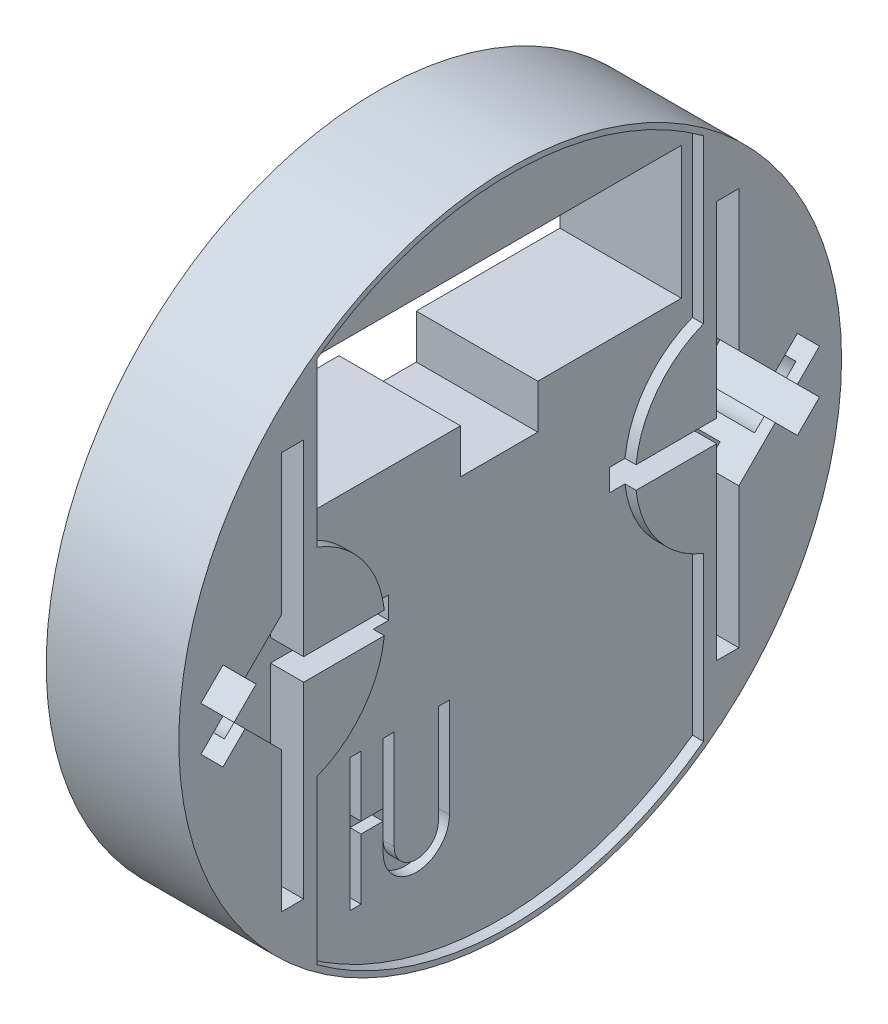
SolidWorks part; units mm, degrees
ref_plane "Front Plane" through (0, 0, 0) normal (0, 0, 1) x (1, 0, 0)
ref_plane "Top Plane" through (0, 0, 0) normal (0, 1, 0) x (1, 0, 0)
ref_plane "Right Plane" through (0, 0, 0) normal (1, 0, 0) x (0, 0, -1)
sketch "Sketch1" plane through (0, 0, 0) normal (1, 0, 0) x (0, 0, -1)
  line L2 (0, -17.4878) -> (0, 20.0189) construction
  circle A0 centre (0, 0) radius 15
  dimension "D1" = 30
extrude "Boss-Extrude1" add sketch "Sketch1" along normal blind 6
sketch "Sketch2" plane through (6, 0, 0) normal (1, 0, 0) x (0, 0, -1)
  line L0 (-8.75, 11.8743) -> (-8.75, 4.5)
  line L1 (0, -13.6401) -> (0, 12.421) construction
  line L2 (-8.75, -4.5) -> (-8.75, -11.8743)
  line L3 (8.75, -4.5) -> (8.75, -11.8743)
  line L4 (8.75, 11.8743) -> (8.75, 4.5)
  arc A0 (-8.75, -11.8743) -> (8.75, -11.8743) centre (0, 0) ccw
  arc A1 (-8.75, -4.5) -> (-8.75, 4.5) centre (-10.5, 0) ccw
  arc A2 (8.75, -4.5) -> (8.75, 4.5) centre (10.5, 0) cw
  arc A3 (8.75, 11.8743) -> (-8.75, 11.8743) centre (0, 0) ccw
  dimension "D1" = 29.5
  dimension "D3" = 8.75
  dimension "D4" = 10.5
  dimension "D2" = 8.75
  dimension "D5" = 9
extrude "Cut-Extrude1" cut sketch "Sketch2" against normal blind 0.5
sketch "Sketch3" plane through (5.5, 0, 0) normal (1, 0, 0) x (0, 0, -1)
  line L4 (-8.25, 11.5) -> (-8.25, 5.5)
  line L5 (-8.25, 5.5) -> (-1.75, 5.5)
  line L6 (-1.75, 5.5) -> (-1.75, 3.5)
  line L7 (-1.75, 3.5) -> (1.75, 3.5)
  line L8 (1.75, 3.5) -> (1.75, 5.5)
  line L9 (1.75, 5.5) -> (8.25, 5.5)
  line L10 (8.25, 5.5) -> (8.25, 11.5)
  line L11 (8.25, 11.5) -> (-8.25, 11.5)
  line L12 (-8.75, 11.8743) -> (-8.75, 4.5) construction
  line L13 (8.75, 4.5) -> (8.75, 11.8743) construction
  circle A5 centre (0, 0) radius 15 construction
  dimension "D1" = 11.5
  dimension "D2" = 0.5
  dimension "D3" = 0.5
  dimension "D4" = 8
  dimension "D5" = 2
  dimension "D6" = 3.5
extrude "Cut-Extrude2" cut sketch "Sketch3" against normal through all
sketch "Sketch4" plane through (6, 0, 0) normal (1, 0, 0) x (0, 0, -1)
  line L0 (-9.35, 9) -> (-9.35, 0.5)
  line L1 (-9.35, -9) -> (-10.35, -9)
  line L2 (-10.35, -9) -> (-10.35, -2.65)
  line L3 (-10.35, -2.65) -> (-12, -1)
  line L4 (-12, -1) -> (-13, -2)
  line L5 (-13, -2) -> (-14, -1)
  line L6 (-14, -1) -> (-13, 0)
  line L7 (-13, 0) -> (-14, 1)
  line L8 (-14, 1) -> (-13, 2)
  line L9 (-13, 2) -> (-12, 1)
  line L10 (-12, 1) -> (-10.35, 2.65)
  line L11 (-10.35, 2.65) -> (-10.35, 9)
  line L12 (-10.35, 9) -> (-9.35, 9)
  line L13 (0, 10.0376) -> (0, -10.6716) construction
  line L14 (-9.35, 0.5) -> (-5, 0.5)
  line L15 (-5, 0.5) -> (-5, -0.5)
  line L16 (-5, -0.5) -> (-9.35, -0.5)
  line L17 (-9.35, -0.5) -> (-9.35, -9)
  line L18 (-8.75, 11.8743) -> (-8.75, 4.5) construction
  line L19 (-5, 0) -> (0, 0) construction
  line L20 (9.35, -0.5) -> (9.35, -9)
  line L21 (5, -0.5) -> (9.35, -0.5)
  line L22 (5, 0.5) -> (5, -0.5)
  line L23 (9.35, 0.5) -> (5, 0.5)
  line L24 (10.35, 9) -> (9.35, 9)
  line L25 (10.35, 2.65) -> (10.35, 9)
  line L26 (12, 1) -> (10.35, 2.65)
  line L27 (13, 2) -> (12, 1)
  line L28 (14, 1) -> (13, 2)
  line L29 (13, 0) -> (14, 1)
  line L30 (14, -1) -> (13, 0)
  line L31 (13, -2) -> (14, -1)
  line L32 (12, -1) -> (13, -2)
  line L33 (10.35, -2.65) -> (12, -1)
  line L34 (10.35, -9) -> (10.35, -2.65)
  line L35 (9.35, -9) -> (10.35, -9)
  line L36 (9.35, 9) -> (9.35, 0.5)
  dimension "D1" = 1
  dimension "D2" = 1
  dimension "D3" = 0.6
  dimension "D4" = 18
  dimension "D5" = 9
  dimension "D6" = 5
  dimension "D7" = 1
  dimension "D8" = 1
  dimension "D9" = 8
  dimension "D10" = 1
extrude "Cut-Extrude4" cut sketch "Sketch4" against normal blind 1.5
sketch "Sketch5" plane through (4.5, 0, 0) normal (1, 0, 0) x (0, 0, -1)
  line L0 (-12, -1) -> (-13, -2)
  line L1 (-13, -2) -> (-14, -1)
  line L2 (-14, -1) -> (-13, 0)
  line L3 (-13, 0) -> (-14, 1)
  line L4 (-14, 1) -> (-13, 2)
  line L5 (-13, 2) -> (-12, 1)
  line L6 (-12, -3.4515) -> (-12, 3.0113) construction
  line L8 (-11, 2) -> (-12, 1)
  line L9 (-10, 1) -> (-11, 2)
  line L10 (-11, 0) -> (-10, 1)
  line L11 (-10, -1) -> (-11, 0)
  line L12 (-11, -2) -> (-10, -1)
  line L13 (-12, -1) -> (-11, -2)
  line L14 (0, -7.7483) -> (0, 8.9458) construction
  line L15 (12, -1) -> (11, -2)
  line L16 (11, -2) -> (10, -1)
  line L17 (10, -1) -> (11, 0)
  line L18 (11, 0) -> (10, 1)
  line L19 (10, 1) -> (11, 2)
  line L20 (11, 2) -> (12, 1)
  line L21 (13, 2) -> (12, 1)
  line L22 (14, 1) -> (13, 2)
  line L23 (13, 0) -> (14, 1)
  line L24 (14, -1) -> (13, 0)
  line L25 (13, -2) -> (14, -1)
  line L26 (12, -1) -> (13, -2)
extrude "Cut-Extrude5" cut sketch "Sketch5" against normal through all
sketch "Sketch6" plane through (5.5, 0, 0) normal (1, 0, 0) x (0, 0, -1)
  line L0 (-6.75, -5) -> (-6.75, -11)
  line L1 (-6.75, -11) -> (-6.25, -11)
  line L2 (-6.25, -11) -> (-6.25, -8.25)
  line L3 (-6.25, -8.25) -> (-5.25, -8.25)
  line L4 (-5.25, -8.25) -> (-5.25, -9.5)
  line L5 (-6.75, -5) -> (-6.25, -5)
  line L6 (-6.25, -5) -> (-6.25, -7.75)
  line L7 (-6.25, -7.75) -> (-5.25, -7.75)
  line L8 (-5.25, -7.75) -> (-5.25, -5)
  line L9 (-5.25, -5) -> (-4.75, -5)
  line L10 (-4.75, -5) -> (-4.75, -9.5)
  line L11 (-2.75, -5) -> (-2.25, -5)
  line L12 (-2.25, -5) -> (-2.25, -9.5)
  line L13 (-2.75, -5) -> (-2.75, -9.5)
  line L14 (-8.75, -4.5) -> (-8.75, -11.8743) construction
  arc A0 (-5.25, -9.5) -> (-2.25, -9.5) centre (-3.75, -9.5) ccw
  arc A1 (-4.75, -9.5) -> (-2.75, -9.5) centre (-3.75, -9.5) ccw
  dimension "D2" = 0.5
  dimension "D8" = 1.25
  dimension "D10" = 0.5
  dimension "D1" = 6
  dimension "D3" = 2.75
  dimension "D4" = 2
  dimension "D5" = 0.5
  dimension "D6" = 3
  dimension "D7" = 1
  dimension "D9" = 5
extrude "Cut-Extrude7" cut sketch "Sketch6" against normal blind 0.5
sketch "Sketch7" plane through (5.5, 0, 0) normal (1, 0, 0) x (0, 0, -1)
  circle A0 centre (-12, 0) radius 1.5
  circle A1 centre (12, 0) radius 1.5
  point P4 (0, 0)
  point P5 (0, 0)
  point P8 (0, 0)
  point P9 (0, 0)
  dimension "D1" = 3
extrude "Cut-Extrude6" cut sketch "Sketch7" against normal blind 10
